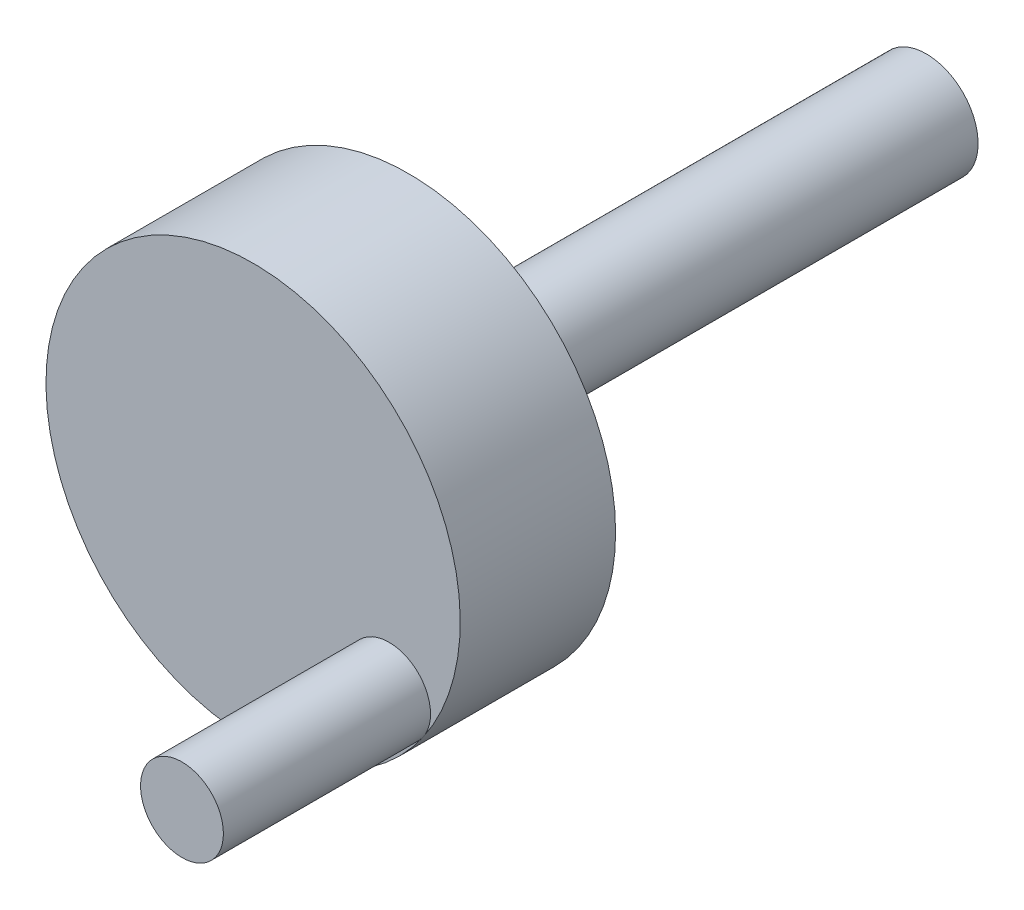
SolidWorks part; units mm, degrees
ref_plane "Front Plane" through (0, 0, 0) normal (0, 0, 1) x (1, 0, 0)
ref_plane "Top Plane" through (0, 0, 0) normal (0, 1, 0) x (1, 0, 0)
ref_plane "Right Plane" through (0, 0, 0) normal (1, 0, 0) x (0, 0, -1)
sketch "Sketch1" plane through (0, 0, 0) normal (0, 0, 1) x (1, 0, 0)
  circle A0 centre (0, 0) radius 20
extrude "Boss-Extrude1" add sketch "Sketch1" along normal blind 15
sketch "Sketch2" plane through (0, 0, 15) normal (0, 0, 1) x (1, 0, 0)
  circle A0 centre (13.1325, -9.1399) radius 4
  dimension "D2" = 8
  dimension "D1" = 16
extrude "Boss-Extrude2" add sketch "Sketch2" along normal blind 20
sketch "Sketch3" plane through (0, 0, 0) normal (0, 0, -1) x (-1, 0, 0)
  circle A0 centre (0, 0) radius 5
extrude "Boss-Extrude3" add sketch "Sketch3" along normal blind 50
